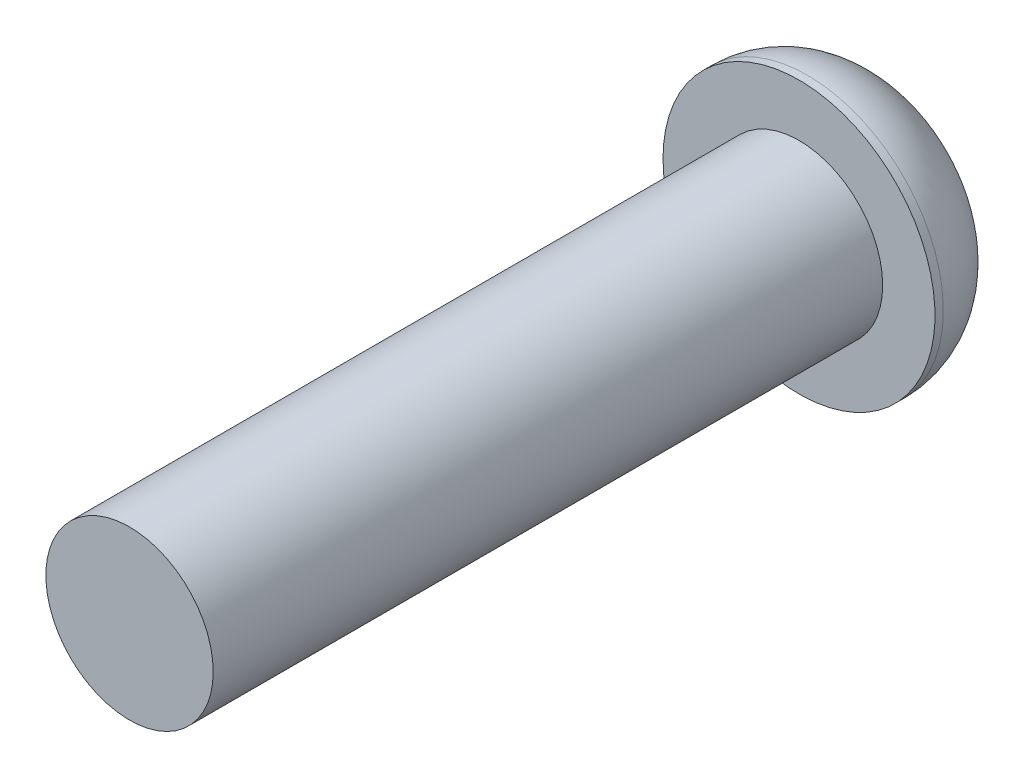
SolidWorks part; units mm, degrees
ref_plane "前视基准面" through (0, 0, 0) normal (0, 0, 1) x (1, 0, 0)
ref_plane "上视基准面" through (0, 0, 0) normal (0, 1, 0) x (1, 0, 0)
ref_plane "右视基准面" through (0, 0, 0) normal (1, 0, 0) x (0, 0, -1)
sketch "草图1" plane through (0, 0, 0) normal (0, 0, 1) x (1, 0, 0)
  circle A0 centre (0, 0) radius 2
  dimension "D1" = 4
extrude "凸台-拉伸1" add sketch "草图1" along normal blind 16
sketch "草图2" plane through (0, 0, 0) normal (0, 0, -1) x (-1, 0, 0)
  circle A0 centre (0, 0) radius 3.25
  dimension "D1" = 6.5
extrude "凸台-拉伸2" add sketch "草图2" along normal blind 2.2
fillet "圆角1" radius 2 1 edges at (-3.25, 0, -2.2)
sketch "草图3" plane through (0, 0, -2.2) normal (0, 0, -1) x (-1, 0, 0)
  line L0 (0, 3.24) -> (0, -3.24) construction
  line L1 (-3.24, 0) -> (3.24, 0) construction
  line L2 (-3.24, 0.25) -> (3.24, 0.25) construction
  line L3 (0.25, 3.24) -> (0.25, -3.24) construction
  line L4 (-3.24, -0.25) -> (3.24, -0.25) construction
  line L5 (-0.25, 3.24) -> (-0.25, -3.24) construction
  line L7 (3.24, 0.25) -> (3.24, -0.25)
  line L8 (-0.25, 3.24) -> (0.25, 3.24)
  line L10 (-0.25, 3.24) -> (-0.25, 0.25)
  line L11 (0.25, 3.24) -> (0.25, 0.25)
  line L12 (3.24, 0.25) -> (0.25, 0.25)
  line L13 (3.24, -0.25) -> (0.25, -0.25)
  line L15 (0.25, -3.24) -> (0.25, -0.25)
  line L16 (-0.25, -3.24) -> (-0.25, -0.25)
  line L17 (0.25, -3.24) -> (-0.25, -3.24)
  line L18 (-3.24, -0.25) -> (-0.25, -0.25)
  line L19 (-3.24, 0.25) -> (-0.25, 0.25)
  line L20 (-3.24, -0.25) -> (-3.24, 0.25)
  line L21 (3.24, 0.25) -> (3.24, -0.25) [skipped]
  circle A1 centre (0, 0) radius 3.24 construction
  dimension "D1" = 0.25
  dimension "D2" = 0.25
  dimension "D3" = 4
extrude "切除-拉伸1" cut sketch "草图3" against normal blind 0.5
